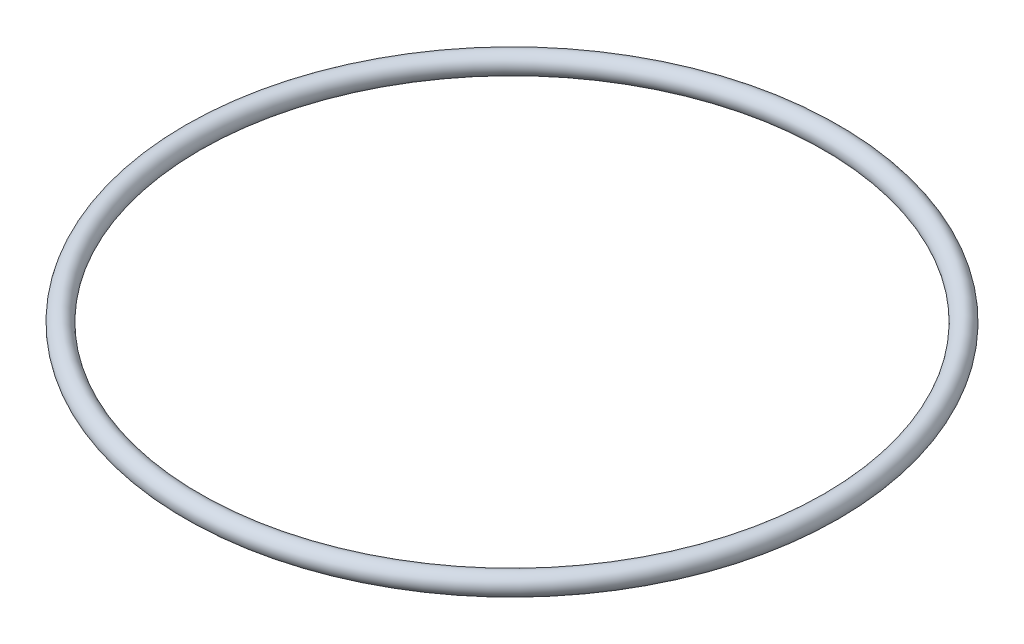
SolidWorks part; units mm, degrees
material "NEOPRENE"
ref_plane "Front Plane" through (0, 0, 0) normal (0, 0, 1) x (1, 0, 0)
ref_plane "Top Plane" through (0, 0, 0) normal (0, 1, 0) x (1, 0, 0)
ref_plane "Right Plane" through (0, 0, 0) normal (1, 0, 0) x (0, 0, -1)
sketch "Sketch1" plane through (0, 0, 0) normal (0, 1, 0) x (1, 0, 0)
  circle A0 centre (0, 0) radius 48.33 construction
  circle A1 centre (0, 0) radius 45.33 construction
  circle A2 centre (0, 0) radius 46.83
  dimension "D2" = 90.66
  dimension "D1" = 3
  dimension "D3" = 1.5
sketch "Sketch2" plane through (0, 0, 0) normal (0, 0, 1) x (1, 0, 0)
  line L1 (46.83, 0) -> (-46.83, 0) construction
  circle A0 centre (-46.83, 0) radius 1.5
  dimension "D1" = 3
  dimension "D2" = 46.83
sweep "Sweep1" add profiles "Sketch2" path "Sketch1"
equation "\"FuelDia\"= 1.6524"
equation "\"OxDia\"= 1.82924"
equation "\"DistOrifice\"= 10"
equation "\"CantAngle\"= 25deg"
equation "\"RadialDistOrifice\"= 60"
equation "\"Chan_amt\"= 35"
equation "\"Chan_wid\"= 3"
equation "\"Chan_heig\"= 5"
equation "\"bolt_diam\"= 15"
equation "\"oring_inner\"=90.66"
equation "\"oring_outer\"=143.374"
equation "\"oring_thickness\"=3"
equation "\"D1@Sketch1\"=\"oring_thickness\""
equation "\"D2@Sketch1\"=\"oring_inner\""
equation "\"D3@Sketch1\"=\"oring_thickness\"/2"
equation "\"D1@Sketch2\"=\"oring_thickness\""
equation "\"D2@Sketch2\"=(\"oring_inner\"/2)+(\"oring_thickness\"/2)"
equation "\"t_plate\"=15"
